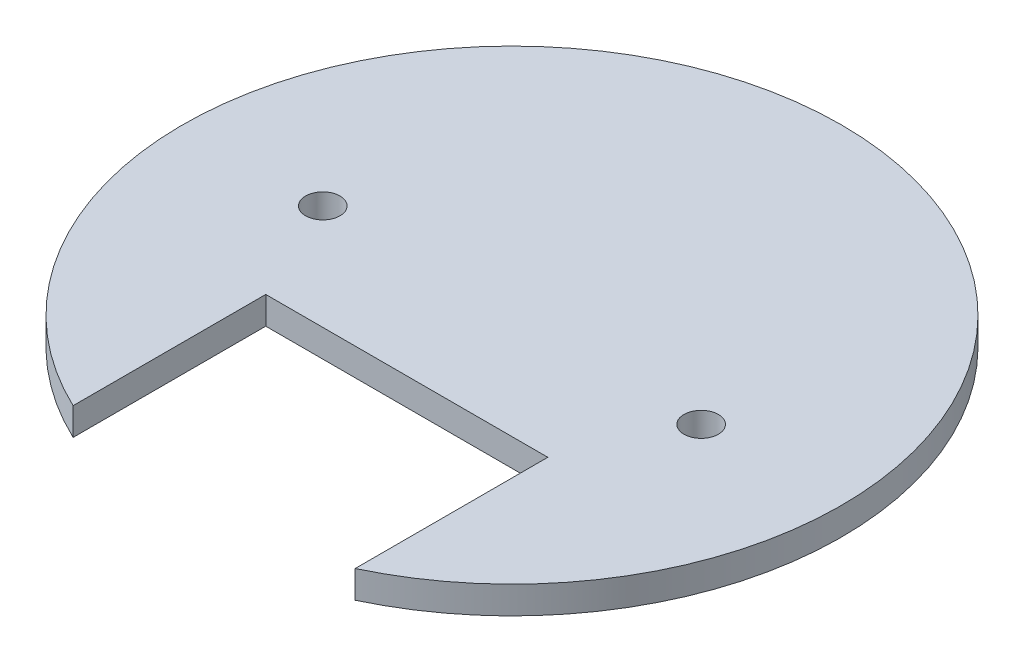
SolidWorks part; units mm, degrees
ref_plane "Front Plane" through (0, 0, 0) normal (0, 0, 1) x (1, 0, 0)
ref_plane "Top Plane" through (0, 0, 0) normal (0, 1, 0) x (1, 0, 0)
ref_plane "Right Plane" through (0, 0, 0) normal (1, 0, 0) x (0, 0, -1)
sketch "Sketch1" plane through (0, 0, 0) normal (0, 1, 0) x (1, 0, 0)
  line L0 (-47.9, 0) -> (47.9, 0) construction
  line L1 (0, 47.9) -> (0, -47.75) construction
  line L2 (-20.5, -43.2916) -> (-20.5, -15.2916)
  line L3 (-20.5, -15.2916) -> (20.5, -15.2916)
  line L4 (20.5, -15.2916) -> (20.5, -43.2916)
  arc A0 (20.5, -43.2916) -> (-20.5, -43.2916) centre (0, 0) ccw
  circle A1 centre (-27.5, 0) radius 2.5
  circle A2 centre (27.5, 0) radius 2.5
  dimension "D1" = 95.8
  dimension "D2" = 5
  dimension "D3" = 55
  dimension "D4" = 28
  dimension "D5" = 41
extrude "Boss-Extrude2" add sketch "Sketch1" along normal blind 4
